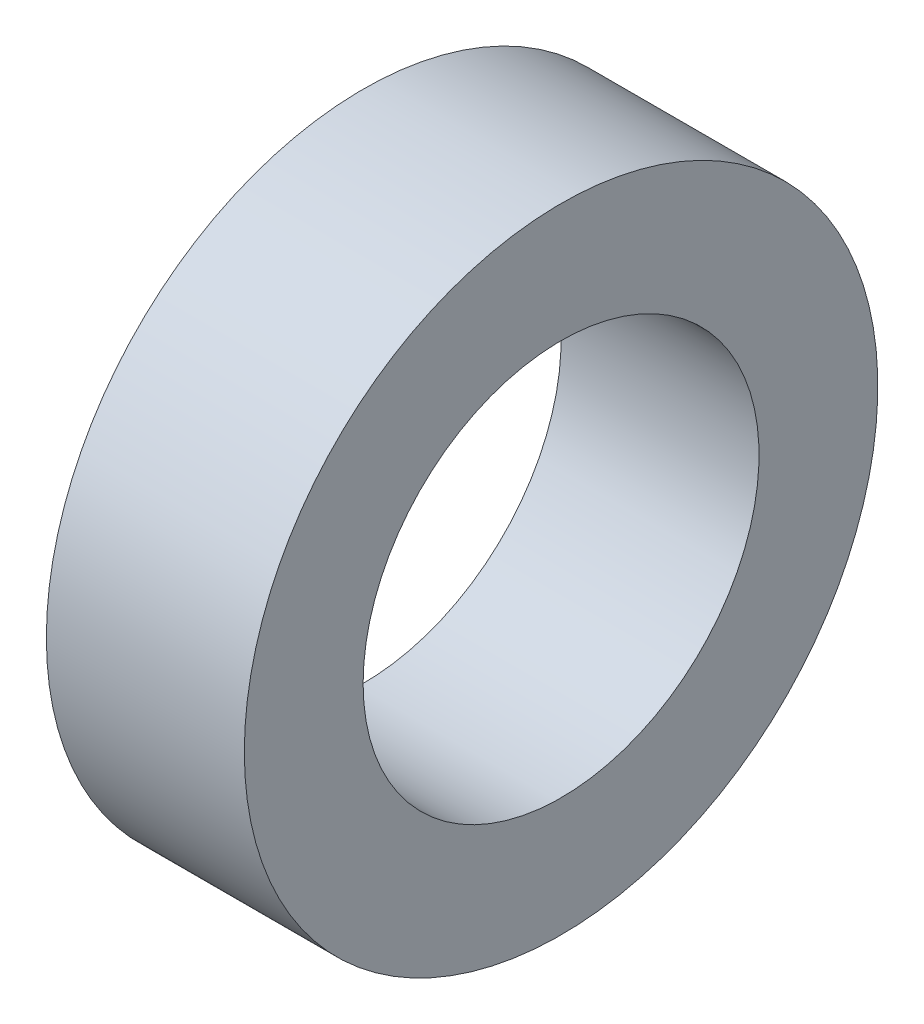
SolidWorks part; units mm, degrees
ref_plane "Front Plane" through (0, 0, 0) normal (0, 0, 1) x (1, 0, 0)
ref_plane "Top Plane" through (0, 0, 0) normal (0, 1, 0) x (1, 0, 0)
ref_plane "Right Plane" through (0, 0, 0) normal (1, 0, 0) x (0, 0, -1)
sketch "Sketch1" plane through (0, 0, 0) normal (0, 0, 1) x (1, 0, 0)
  line L0 (0, 0) -> (3.326, 0) construction
  line L2 (0, 2.5) -> (2.5, 2.5)
  line L3 (0, 2.5) -> (0, 4)
  line L4 (0, 4) -> (2.5, 4)
  line L5 (2.5, 2.5) -> (2.5, 4)
  point P7 (0, 0)
  dimension "D1" = 2.5
  dimension "D2" = 4
  dimension "D3" = 2.5
revolve "Revolve1" add sketch "Sketch1" angle 360 about L0
